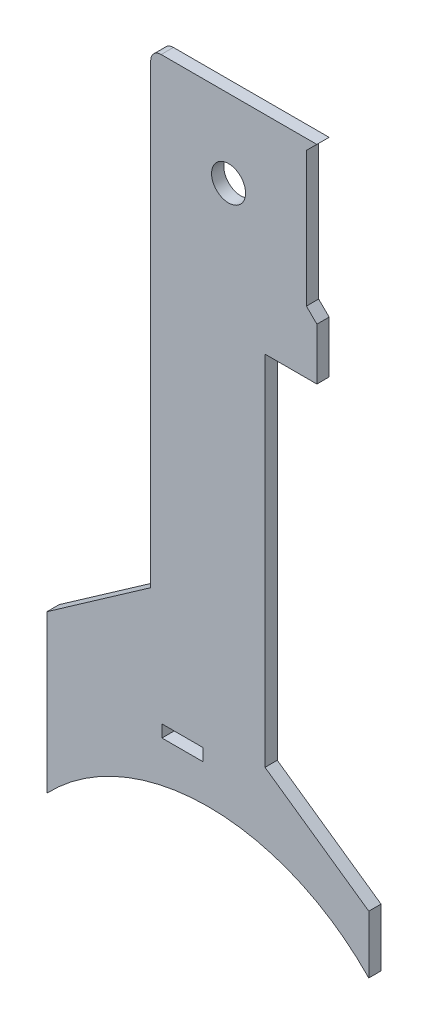
SolidWorks part; units mm, degrees
material "6063-T6"
ref_plane "Front Plane" through (0, 0, 0) normal (0, 0, 1) x (1, 0, 0)
ref_plane "Top Plane" through (0, 0, 0) normal (0, 1, 0) x (1, 0, 0)
ref_plane "Right Plane" through (0, 0, 0) normal (1, 0, 0) x (0, 0, -1)
sketch "Sketch1" plane through (0, 0, 0) normal (0, 0, 1) x (-1, 0, 0)
  line L3 (16.6878, -36.83) -> (54.8103, -36.83)
  line L4 (57.3503, -34.29) -> (57.3503, 77.47)
  line L5 (16.6802, 1.27) -> (16.6802, 13.97)
  line L6 (16.6802, 13.97) -> (29.3802, 13.97)
  line L7 (29.3802, 13.97) -> (29.3802, 90.17)
  line L8 (57.3503, 77.47) -> (82.7503, 95.25)
  line L9 (3.9802, 119.3493) -> (29.3802, 101.5641)
  line L10 (82.7503, 95.25) -> (82.7503, 133.7211)
  line L11 (29.3802, 101.5641) -> (29.3802, 90.17)
  line L13 (3.9802, 119.3493) -> (3.9802, 133.5205)
  line L108 (19.2503, -1.27) -> (16.6802, 1.27)
  line L142 (16.6878, -36.83) -> (19.2503, -34.29)
  line L143 (19.2503, -34.29) -> (19.2503, -1.27)
  arc A0 (54.8103, -36.83) -> (57.3503, -34.29) centre (54.8103, -34.29) ccw
  arc A3 (3.9802, 133.5205) -> (82.7503, 133.7211) centre (43.2689, 171.45) ccw
  point P8 (57.3503, -36.83)
  dimension "D1" = 38.1
  dimension "D3" = 2.54
  dimension "D9" = 125
  dimension "D10" = 33.02
  dimension "D6" = 124.992
  dimension "D2" = 114.3
  dimension "D4" = 12.7
  dimension "D5" = 12.7
  dimension "D7" = 25.4
  dimension "D8" = 25.4
  dimension "D11" = 38.1
extrude "Boss-Extrude1" add sketch "Sketch1" along normal blind 3 contours L108 L5 L6 L7 L11 L9 L13 A3 L10 L8 L4 A0 L3 L142 L143
sketch "Sketch2" plane through (0, 0, 3) normal (0, 0, 1) x (1, 0, 0)
  line L0 (-57.3503, 34.29) -> (-57.3503, -77.47) construction
  line L1 (-16.6878, 36.83) -> (-54.8103, 36.83) construction
  circle A0 centre (-38.3003, 17.78) radius 4.1656
  dimension "D1" = 19.05
  dimension "D2" = 19.05
extrude "Cut-Extrude1" cut sketch "Sketch2" against normal through all
sketch "Sketch3" plane through (0, 0, 3) normal (0, 0, 1) x (1, 0, 0)
  line L1 (-44.6021, -107.9614) -> (-54.6021, -107.9614)
  line L2 (-44.6021, -107.9614) -> (-44.6021, -104.9614)
  line L3 (-44.6021, -104.9614) -> (-54.6021, -104.9614)
  line L4 (-54.6021, -107.9614) -> (-54.6021, -104.9614)
  line L5 (-44.6021, -107.9614) -> (-54.6021, -104.9614) construction
  line L6 (-44.6021, -104.9614) -> (-54.6021, -107.9614) construction
  point P0 (-49.6021, -106.4614)
  dimension "D1" = 3
  dimension "D2" = 10
extrude "Cut-Extrude2" cut sketch "Sketch3" against normal through all
